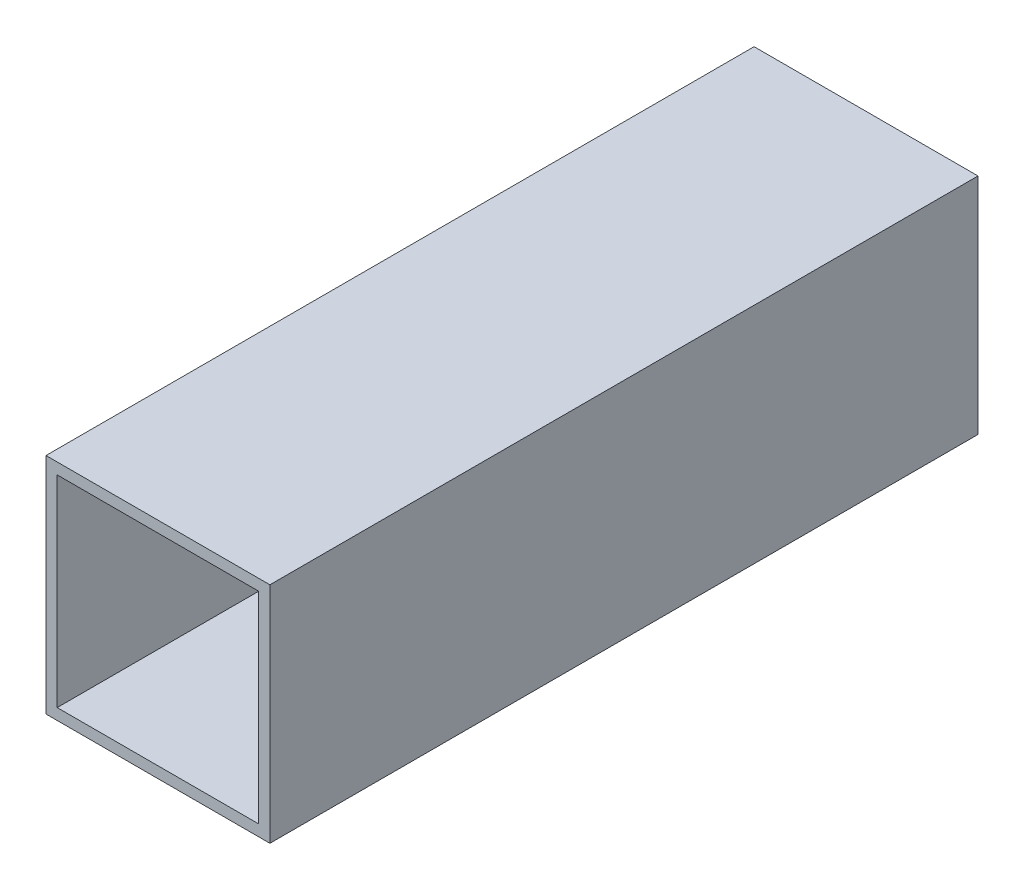
SolidWorks part; units mm, degrees
material "Aleación 1060"
ref_plane "Alzado" through (0, 0, 0) normal (0, 0, 1) x (1, 0, 0)
ref_plane "Planta" through (0, 0, 0) normal (0, 1, 0) x (1, 0, 0)
ref_plane "Vista lateral" through (0, 0, 0) normal (1, 0, 0) x (0, 0, -1)
sketch "Croquis1" plane through (0, 0, 0) normal (0, 0, 1) x (1, 0, 0)
  line L1 (20, -20) -> (-20, -20)
  line L2 (20, -20) -> (20, 20)
  line L3 (20, 20) -> (-20, 20)
  line L4 (-20, -20) -> (-20, 20)
  line L5 (20, -20) -> (-20, 20) construction
  line L6 (20, 20) -> (-20, -20) construction
  point P0 (0, 0)
  dimension "D1" = 40
  dimension "D2" = 40
extrude "Extruir-Lámina1" add sketch "Croquis1" along normal blind 126.5 thin
